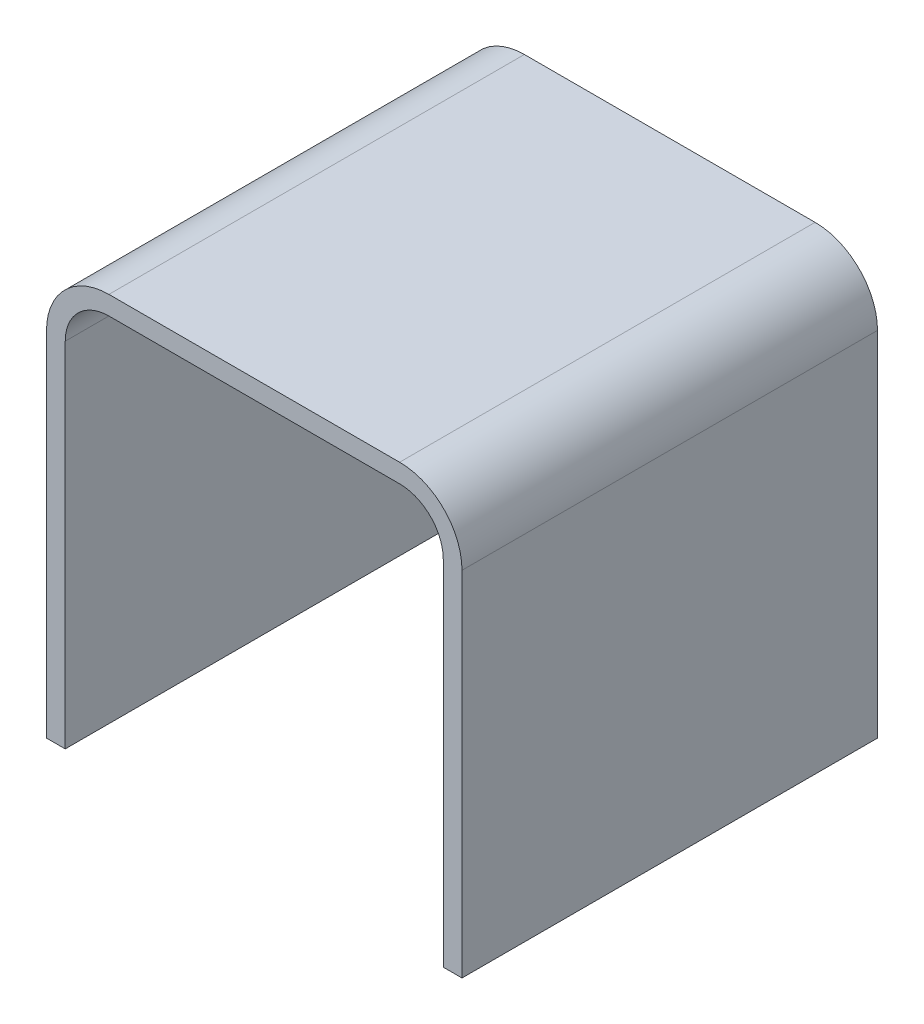
SolidWorks part; units mm, degrees
ref_plane "Piano frontale" through (0, 0, 0) normal (0, 0, 1) x (1, 0, 0)
ref_plane "Piano superiore" through (0, 0, 0) normal (0, 1, 0) x (1, 0, 0)
ref_plane "Piano destro" through (0, 0, 0) normal (1, 0, 0) x (0, 0, -1)
sketch "Schizzo1" plane through (0, 0, 0) normal (0, 0, 1) x (1, 0, 0)
  line L1 (33.3, -33.3) -> (-33.3, -33.3)
  line L2 (33.3, -33.3) -> (33.3, 33.3)
  line L3 (33.3, 33.3) -> (-33.3, 33.3)
  line L4 (-33.3, -33.3) -> (-33.3, 33.3)
  line L5 (33.3, -33.3) -> (-33.3, 33.3) construction
  line L6 (33.3, 33.3) -> (-33.3, -33.3) construction
  point P0 (0, 0)
  dimension "D1" = 66.6
  dimension "D2" = 66.6
extrude "Estrusione-Estrusione1" add sketch "Schizzo1" along normal blind 3
sketch "Schizzo2" plane through (0, 0, 3) normal (0, 0, 1) x (1, 0, 0)
  line L0 (-33.3, -33.3) -> (33.3, -33.3) construction
  line L1 (-33.3, 33.3) -> (-30.3, 33.3)
  line L2 (-33.3, 33.3) -> (-33.3, -33.3)
  line L3 (-33.3, -33.3) -> (-30.3, -33.3)
  line L4 (-30.3, 33.3) -> (-30.3, -33.3)
  line L6 (33.3, 33.3) -> (30.3, 33.3)
  line L7 (33.3, 33.3) -> (33.3, -33.3)
  line L8 (33.3, -33.3) -> (30.3, -33.3)
  line L9 (30.3, 33.3) -> (30.3, -33.3)
  dimension "D1" = 3
  dimension "D2" = 3
extrude "Estrusione-Estrusione2" add sketch "Schizzo2" along normal blind 63.6
sketch "Schizzo3" plane through (0, -33.3, 0) normal (0, -1, 0) x (1, 0, 0)
  line L0 (-33.3, 66.6) -> (-33.3, 0) construction
  line L1 (-33.3, 0) -> (33.3, 0) construction
  line L2 (33.3, 66.6) -> (33.3, 0) construction
  line L3 (-33.3, 5) -> (-33.3, 0)
  line L4 (-33.3, 0) -> (-28.3, 0)
  line L5 (33.3, 0) -> (33.3, 5)
  line L6 (28.3, 0) -> (33.3, 0)
  arc A0 (-33.3, 5) -> (-28.3, 0) centre (-28.3, 5) ccw
  arc A1 (28.3, 0) -> (33.3, 5) centre (28.3, 5) ccw
  dimension "D1" = 10
  dimension "D2" = 10
extrude "Taglio-Estrusione1" [suppressed] cut sketch "Schizzo3" against normal blind 66.6
sketch "Schizzo4" plane through (0, -33.3, 0) normal (0, -1, 0) x (1, 0, 0)
  line L0 (-30.3, 66.6) -> (-30.3, 3) construction
  line L1 (-30.3, 3) -> (30.3, 3) construction
  line L2 (30.3, 66.6) -> (30.3, 3) construction
  line L3 (-30.3, 6.5) -> (-30.3, 3)
  line L4 (-30.3, 3) -> (-26.8, 3)
  line L5 (30.3, 6.5) -> (30.3, 3)
  line L6 (30.3, 3) -> (26.8, 3)
  arc A0 (-30.3, 6.5) -> (-26.8, 3) centre (-26.8, 6.5) ccw
  arc A1 (26.8, 3) -> (30.3, 6.5) centre (26.8, 6.5) ccw
  dimension "D1" = 7
  dimension "D2" = 7
extrude "Estrusione-Estrusione3" [suppressed] add sketch "Schizzo4" against normal blind 66.6
sketch "Schizzo6" plane through (0, 0, 3) normal (0, 0, 1) x (1, 0, 0)
  line L0 (30.3, 33.3) -> (30.3, -33.3) construction
  line L1 (-30.3, 33.3) -> (30.3, 33.3)
  line L2 (-30.3, 33.3) -> (-30.3, 30.3)
  line L3 (-30.3, 30.3) -> (30.3, 30.3)
  line L4 (30.3, 33.3) -> (30.3, 30.3)
  dimension "D1" = 3
extrude "Estrusione-Estrusione4" add sketch "Schizzo6" along normal blind 63.6
sketch "Schizzo7" plane through (0, 0, 66.6) normal (0, 0, 1) x (1, 0, 0)
  line L0 (33.3, 33.3) -> (-33.3, 33.3) construction
  line L1 (-33.3, 33.3) -> (-33.3, -33.3) construction
  line L2 (33.3, -33.3) -> (33.3, 33.3) construction
  line L4 (-33.3, 23.3) -> (-33.3, 33.3)
  line L5 (-33.3, 33.3) -> (-23.3, 33.3)
  line L6 (33.3, 33.3) -> (33.3, 23.3)
  line L7 (23.3, 33.3) -> (33.3, 33.3)
  arc A0 (-23.3, 33.3) -> (-33.3, 23.3) centre (-23.3, 23.3) ccw
  arc A1 (33.3, 23.3) -> (23.3, 33.3) centre (23.3, 23.3) ccw
  dimension "D1" = 20
  dimension "D2" = 20
extrude "Taglio-Estrusione2" cut sketch "Schizzo7" against normal blind 66.6
sketch "Schizzo8" plane through (0, 0, 3) normal (0, 0, 1) x (1, 0, 0)
  line L0 (-30.3, 30.3) -> (30.3, 30.3) construction
  line L1 (-30.3, -33.3) -> (-30.3, 30.3) construction
  line L2 (30.3, 30.3) -> (30.3, -33.3) construction
  line L3 (-30.3, 23.3) -> (-30.3, 30.3)
  line L4 (-30.3, 30.3) -> (-23.3, 30.3)
  line L5 (30.3, 30.3) -> (30.3, 23.3)
  line L6 (23.3, 30.3) -> (30.3, 30.3)
  arc A0 (-23.3, 30.3) -> (-30.3, 23.3) centre (-23.3, 23.3) ccw
  arc A1 (30.3, 23.3) -> (23.3, 30.3) centre (23.3, 23.3) ccw
  dimension "D1" = 14
  dimension "D2" = 14
extrude "Estrusione-Estrusione5" add sketch "Schizzo8" along normal blind 63.6
sketch "Schizzo9" plane through (0, 27.3, 3) normal (0, 0, 1) x (1, 0, 0)
  circle A0 centre (0, -14.8) radius 6
  point P2 (4.5746, 11.6328)
  point P4 (0, 0)
  dimension "D1" = 12
  dimension "D2" = 12.5
extrude "Taglio-Estrusione4" cut sketch "Schizzo9" against normal through all contours A0
